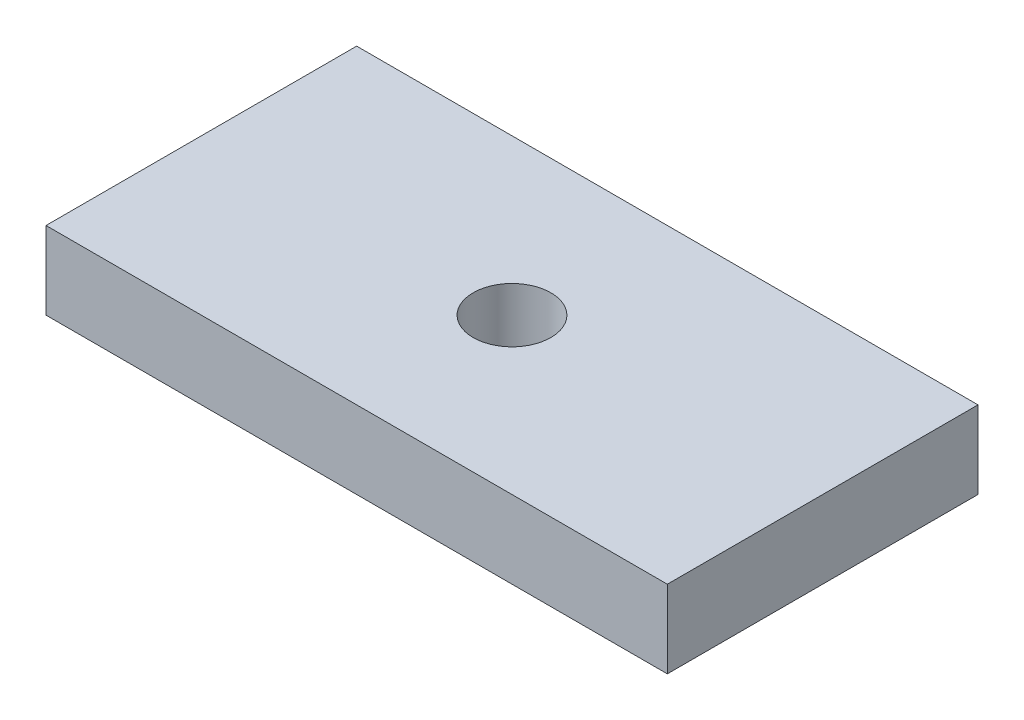
SolidWorks part; units mm, degrees
ref_plane "Front Plane" through (0, 0, 0) normal (0, 0, 1) x (1, 0, 0)
ref_plane "Top Plane" through (0, 0, 0) normal (0, 1, 0) x (1, 0, 0)
ref_plane "Right Plane" through (0, 0, 0) normal (1, 0, 0) x (0, 0, -1)
sketch "Sketch1" plane through (0, 0, 0) normal (0, 1, 0) x (1, 0, 0)
  line L1 (0, 0) -> (25.4, 0)
  line L2 (0, 0) -> (0, 12.7)
  line L3 (0, 12.7) -> (25.4, 12.7)
  line L4 (25.4, 0) -> (25.4, 12.7)
  dimension "D1" = 25.4
  dimension "D2" = 12.7
extrude "Boss-Extrude1" add sketch "Sketch1" along normal blind 3.175
sketch "Sketch2" plane through (0, 3.175, 0) normal (0, 1, 0) x (1, 0, 0)
  line L0 (12.7, 12.7) -> (12.7, 0) construction
  line L1 (25.4, 12.7) -> (0, 12.7) construction
  line L2 (0, 0) -> (25.4, 0) construction
  circle A0 centre (12.7, 6.35) radius 1.5875
  point P2 (0, 0)
  dimension "D1" = 3.175
extrude "Cut-Extrude1" cut sketch "Sketch2" against normal through all
